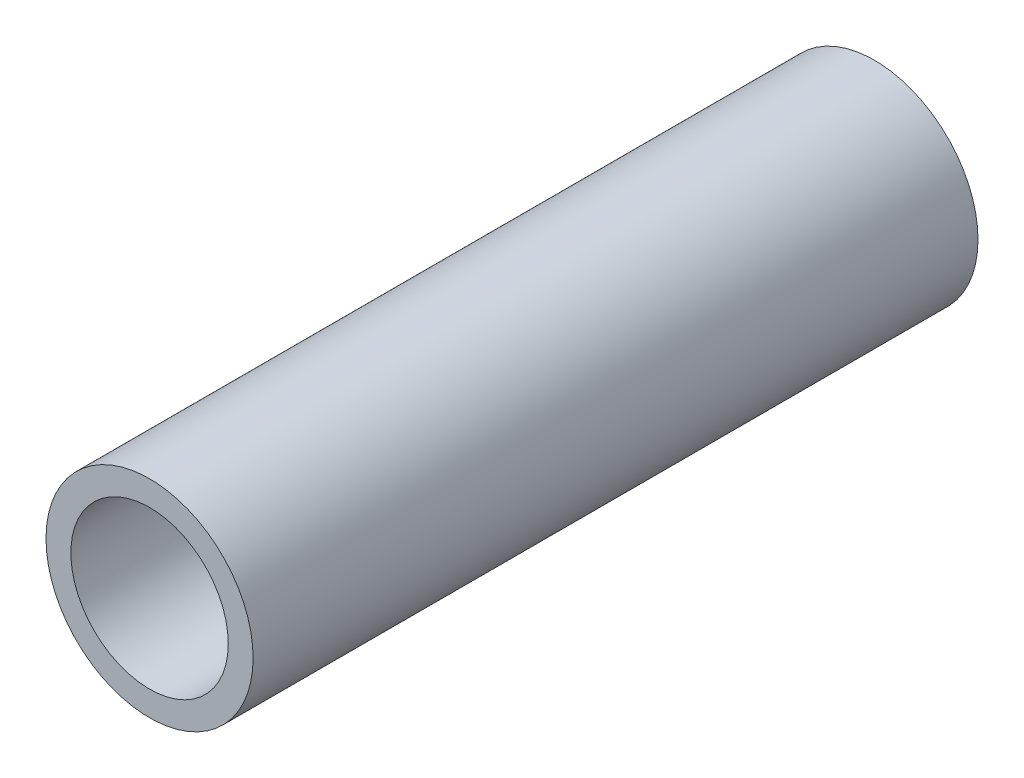
SolidWorks part; units mm, degrees
ref_plane "Front Plane" through (0, 0, 0) normal (0, 0, 1) x (1, 0, 0)
ref_plane "Top Plane" through (0, 0, 0) normal (0, 1, 0) x (1, 0, 0)
ref_plane "Right Plane" through (0, 0, 0) normal (1, 0, 0) x (0, 0, -1)
sketch "Sketch2" plane through (0, 0, 0) normal (0, 0, 1) x (1, 0, 0)
  circle A0 centre (0, 0) radius 10
  circle A1 centre (0, 0) radius 6.1
  dimension "D1" = 20
  dimension "D2" = 12.2
extrude "Boss-Extrude1" add sketch "Sketch2" along normal blind 25
sketch "Sketch3" plane through (0, 0, 25) normal (0, 0, 1) x (1, 0, 0)
  circle A0 centre (0, 0) radius 10
  dimension "D1" = 20
extrude "Boss-Extrude2" add sketch "Sketch3" along normal blind 45
sketch "Sketch4" plane through (0, 0, 70) normal (0, 0, 1) x (1, 0, 0)
  circle A0 centre (0, 0) radius 7.6
  dimension "D1" = 15.2
extrude "Cut-Extrude1" cut sketch "Sketch4" against normal blind 45
